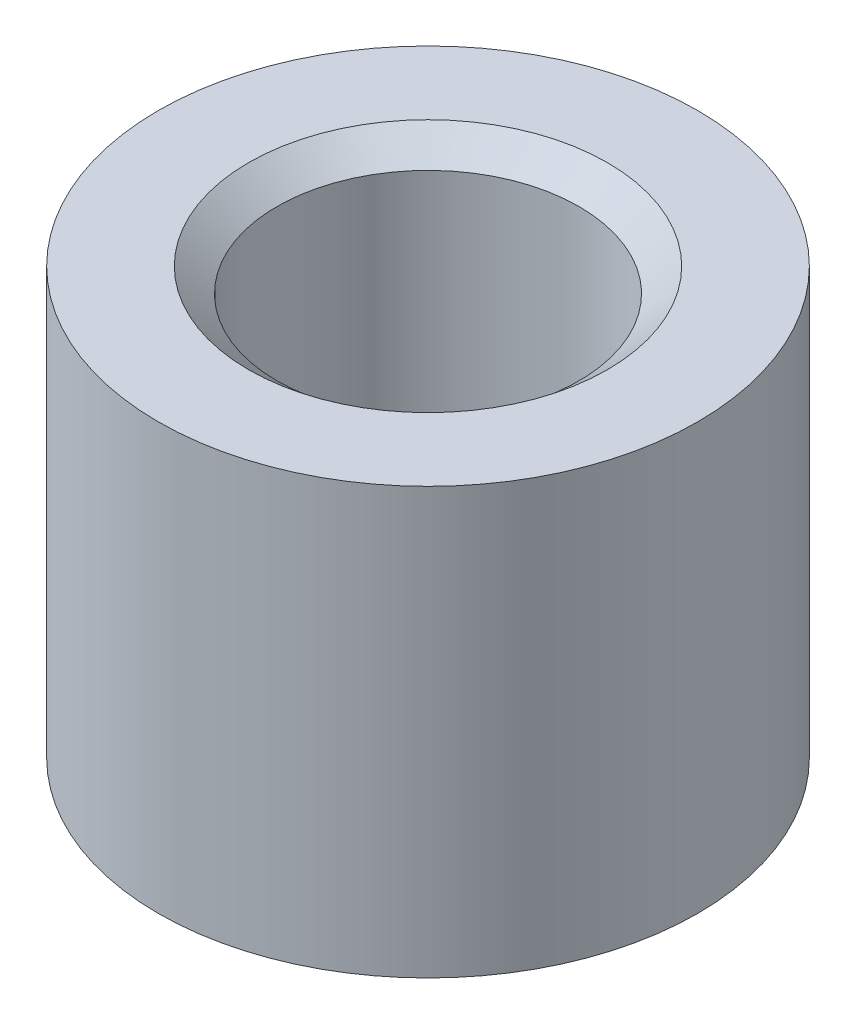
SolidWorks part; units mm, degrees
material "Brass"
ref_plane "Front" through (0, 0, 0) normal (0, 0, 1) x (1, 0, 0)
ref_plane "Top" through (0, 0, 0) normal (0, 1, 0) x (1, 0, 0)
ref_plane "Right" through (0, 0, 0) normal (1, 0, 0) x (0, 0, -1)
sketch "Sketch1" plane through (0, 0, 0) normal (0, 1, 0) x (1, 0, 0)
  circle A0 centre (0, 0) radius 6.0325
  dimension "D1" = 12.065
extrude "Boss-Extrude1" add sketch "Sketch1" along normal blind 9.525
hole_wizard "1/4 Clearance Hole1" positions "Sketch2" profile "Sketch3" hole size "1/4" standard "ANSI Inch" end condition through all
sketch "Sketch2" plane through (0, 9.525, 0) normal (0, 1, 0) x (1, 0, 0)
  point P0 (0, 0)
sketch "Sketch3" plane through (0, 9.525, 0) normal (1, 0, 0) x (0, 0, 1)
  line L0 (0, 0) -> (0, 9.525)
  line L1 (0, 9.525) -> (3.3782, 9.525)
  line L2 (3.3782, 9.525) -> (3.3782, 0.5328)
  line L3 (3.3782, 0.5328) -> (4.0132, 0)
  line L5 (4.0132, 0) -> (0, 0)
  line L6 (-3.3782, 0.5328) -> (-4.0132, 0) construction
  line L11 (0, -6.35) -> (0, 107.95) construction
  dimension "Thru Hole Dia." = 6.7564
  dimension "Thru Hole Depth" = 9.525
  dimension "Near C'Sink Dia." = 8.0264
  dimension "Near C'Sink Angle" = 100
